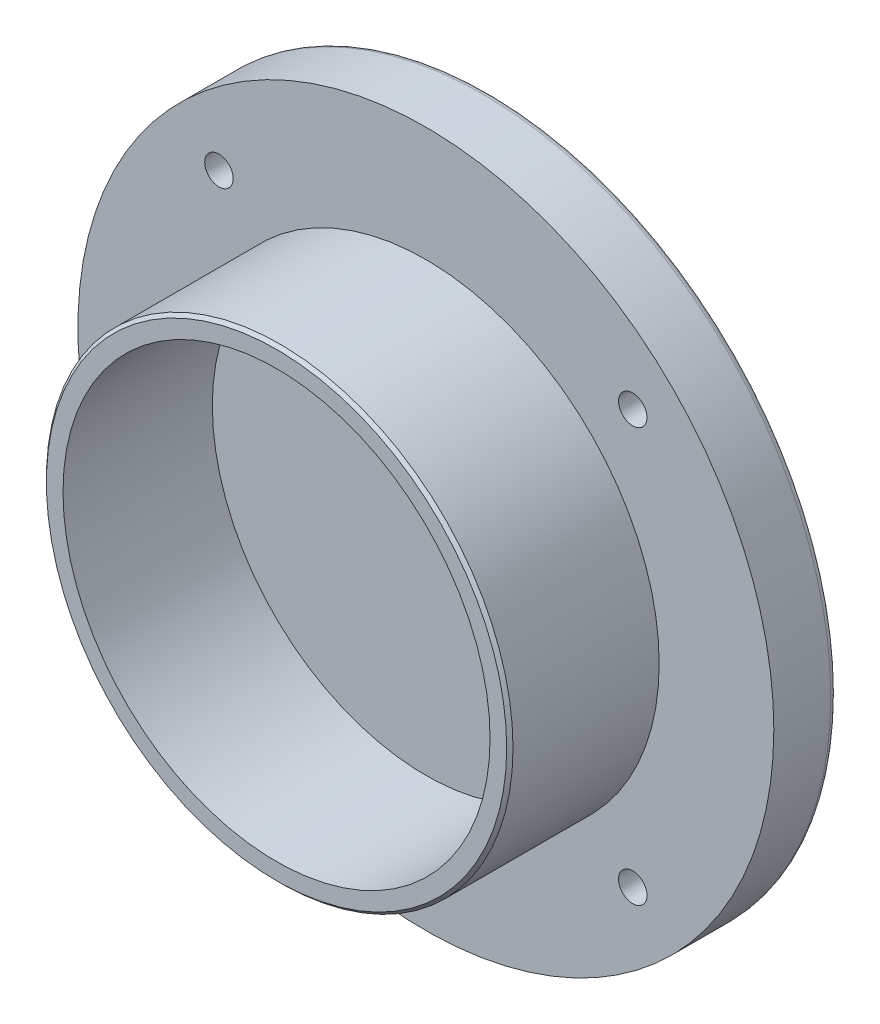
SolidWorks part; units mm, degrees
ref_plane "Piano frontale" through (0, 0, 0) normal (0, 0, 1) x (1, 0, 0)
ref_plane "Piano superiore" through (0, 0, 0) normal (0, 1, 0) x (1, 0, 0)
ref_plane "Piano destro" through (0, 0, 0) normal (1, 0, 0) x (0, 0, -1)
sketch "Schizzo1" plane through (0, 0, 0) normal (0, 0, 1) x (1, 0, 0)
  circle A0 centre (0, 0) radius 110
  dimension "D1" = 220
extrude "Estrusione-Estrusione1" add sketch "Schizzo1" against normal blind 20
sketch "Schizzo2" plane through (0, 0, 0) normal (0, 0, 1) x (1, 0, 0)
  circle A0 centre (0, 0) radius 73.75
  circle A1 centre (0, 0) radius 67.5
  dimension "D1" = 135
  dimension "D2" = 147.5
extrude "Estrusione-Estrusione2" add sketch "Schizzo2" along normal blind 47.2 separate body
sketch "Schizzo3" plane through (0, 0, -20) normal (0, 0, -1) x (-1, 0, 0)
  line L0 (0, 133.8031) -> (0, -132.3759) construction
  line L1 (0, 0) -> (-118.6155, 118.6155) construction
  circle A0 centre (0, 0) radius 73.75 construction
  circle A1 centre (0, 0) radius 73.75 construction
  dimension "D1" = 45
sketch "Schizzo6" plane through (0, 0, -20) normal (0, 0, -1) x (-1, 0, 0)
  circle A0 centre (0, 0) radius 92.5 construction
  dimension "D1" = 185
hole_wizard "Foro lamato per Vite M8 a testa cilindrica piana-1" positions "Schizzo8" profile "Schizzo7" counterbore size "M8" standard "ISO" end condition through all
sketch "Schizzo8" plane through (0, 0, -20) normal (0, 0, -1) x (-1, 0, 0)
  line L0 (0, 0) -> (-118.6155, 118.6155) construction
  circle A0 centre (0, 0) radius 92.5 construction
  point P0 (-65.4074, 65.4074)
sketch "Schizzo7" plane through (65.4074, 65.4074, -20) normal (1, 0, 0) x (0, 1, 0)
  line L0 (0, 0) -> (0, 20)
  line L1 (0, 20) -> (4.5, 20)
  line L3 (4.5, 20) -> (4.5, 8)
  line L4 (4.5, 8) -> (7.5, 8)
  line L5 (7.5, 8) -> (7.5, 0)
  line L7 (7.5, 0) -> (0, 0)
  line L11 (0, -6.35) -> (0, 107.95) construction
  dimension "Thru Hole Dia." = 9
  dimension "Thru Hole Depth" = 20
  dimension "C'Bore Dia." = 15
  dimension "C'Bore Depth" = 8
pattern_circular "RipetizioneCircolare2" count 4 over 360 about axis through (0, 0, 0) along (0, 0, 1) of "Foro lamato per Vite M8 a testa cilindrica piana-1"
fillet "Raccordo1" radius 2 1 edges at (110, 0, -20)
chamfer "Smusso1" distance 1 angle 45 1 edges at (73.75, 0, 47.2)
